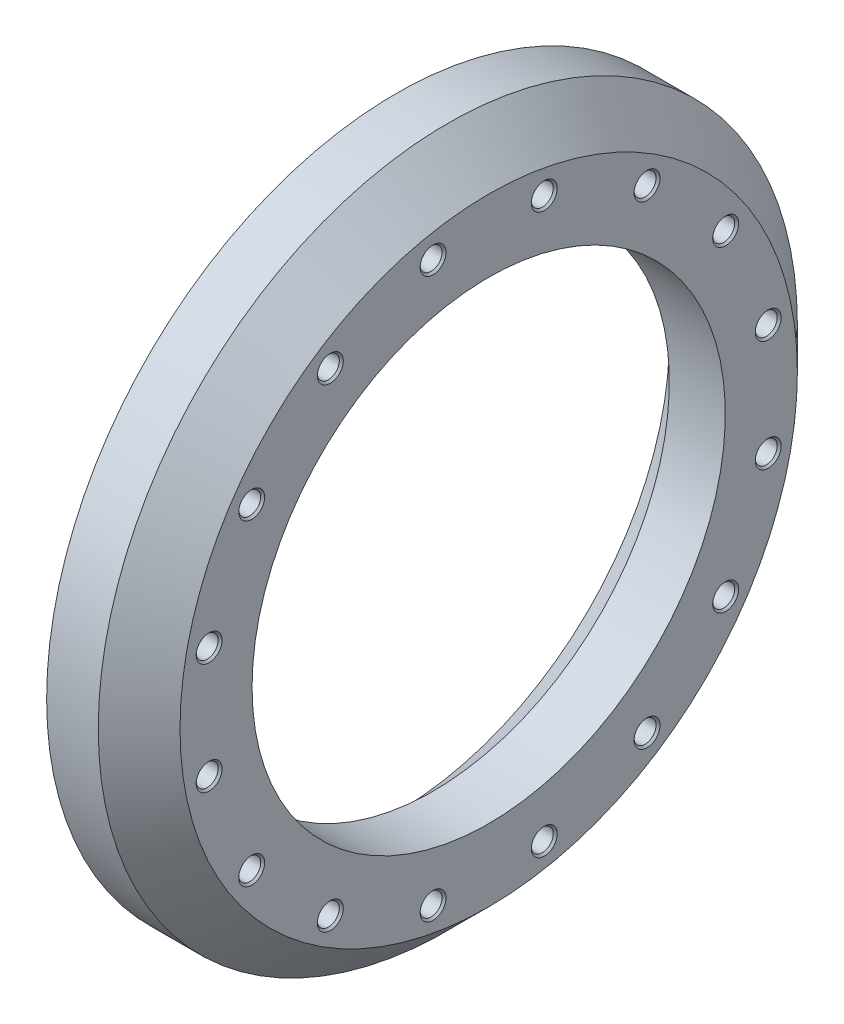
SolidWorks part; units mm, degrees
ref_plane "Front Plane" through (0, 0, 0) normal (0, 0, 1) x (1, 0, 0)
ref_plane "Top Plane" through (0, 0, 0) normal (0, 1, 0) x (1, 0, 0)
ref_plane "Right Plane" through (0, 0, 0) normal (1, 0, 0) x (0, 0, -1)
sketch "Sketch1" plane through (0, 0, 0) normal (0, 0, 1) x (1, 0, 0)
  line L0 (0, 0) -> (182.7212, 0) construction
  line L2 (0, 162.5) -> (0, 127)
  line L5 (17, 110) -> (43, 110)
  line L6 (43, 110) -> (43, 143.5)
  line L7 (0, 162.5) -> (24, 162.5)
  line L8 (24, 162.5) -> (43, 143.5)
  line L10 (0, 127) -> (17, 110)
  dimension "D1" = 325
  dimension "D2" = 254
  dimension "D3" = 43
  dimension "D4" = 45
  dimension "D5" = 19
  dimension "D7" = 220
revolve "Revolve1" add sketch "Sketch1" angle 360 about L0
sketch "Sketch2" plane through (0, 0, 0) normal (-1, 0, 0) x (0, 0, 1)
  line L0 (0, 0) -> (25.8495, 129.954) construction
  circle A0 centre (0, 0) radius 152 construction
  circle A1 centre (0, 0) radius 132.5 construction
  dimension "D1" = 304
  dimension "D2" = 265
  dimension "D3" = 11.25
hole_wizard "M12 Tapped Hole1" positions "Sketch3" profile "Sketch4" tap size "M12" standard "ISO"
sketch "Sketch3" plane through (0, 0, 0) normal (-1, 0, 0) x (0, 0, 1)
  circle A0 centre (0, 0) radius 152 construction
  point P0 (0, 152)
sketch "Sketch4" plane through (0, 152, 0) normal (0, 1, 0) x (0, 0, 1)
  line L0 (0, 0) -> (0, 26.3144)
  line L1 (0, 26.3144) -> (5.1, 23.25)
  line L2 (5.1, 23.25) -> (5.1, 0.925)
  line L3 (5.1, 0.925) -> (6.025, 0)
  line L5 (6.025, 0) -> (0, 0)
  line L6 (-5.1, 0.925) -> (-6.025, 0) construction
  line L10 (0, 26.3144) -> (-5.1, 23.25) construction
  line L11 (0, -6.35) -> (0, 107.95) construction
  dimension "Tap Drill Dia." = 10.2
  dimension "Tap Drill Depth" = 23.25
  dimension "Near C'Sink Dia." = 12.05
  dimension "Near C'Sink Angle" = 90
  dimension "Drill Angle" = 118
cosmetic thread "Hole Thread1" parameters "D1"=18, "D2"=12
pattern_circular "CirPattern1" count 16 over 360 about axis through (0, 0, 0) along (1, 0, 0) of "M12 Tapped Hole1"
cosmetic thread "Hole Thread2" parameters "D1"=18, "D2"=12
cosmetic thread "Hole Thread3" parameters "D1"=18, "D2"=12
cosmetic thread "Hole Thread4" parameters "D1"=18, "D2"=12
cosmetic thread "Hole Thread5" parameters "D1"=18, "D2"=12
cosmetic thread "Hole Thread6" parameters "D1"=18, "D2"=12
cosmetic thread "Hole Thread7" parameters "D1"=18, "D2"=12
cosmetic thread "Hole Thread8" parameters "D1"=18, "D2"=12
cosmetic thread "Hole Thread9" parameters "D1"=18, "D2"=12
cosmetic thread "Hole Thread10" parameters "D1"=18, "D2"=12
cosmetic thread "Hole Thread11" parameters "D1"=18, "D2"=12
cosmetic thread "Hole Thread12" parameters "D1"=18, "D2"=12
cosmetic thread "Hole Thread13" parameters "D1"=18, "D2"=12
cosmetic thread "Hole Thread14" parameters "D1"=18, "D2"=12
cosmetic thread "Hole Thread15" parameters "D1"=18, "D2"=12
cosmetic thread "Hole Thread16" parameters "D1"=18, "D2"=12
hole_wizard "M12 Tapped Hole2" positions "Sketch5" profile "Sketch6" tap size "M12" standard "ISO"
sketch "Sketch5" plane through (43, 0, 0) normal (1, 0, 0) x (0, 0, -1)
  point P4 (-25.8495, 129.954)
sketch "Sketch6" plane through (43, 129.954, 25.8495) normal (0, 1, 0) x (0, 0, -1)
  line L0 (0, 0) -> (0, 32.3144)
  line L1 (0, 32.3144) -> (5.1, 29.25)
  line L2 (5.1, 29.25) -> (5.1, 0.925)
  line L3 (5.1, 0.925) -> (6.025, 0)
  line L5 (6.025, 0) -> (0, 0)
  line L6 (-5.1, 0.925) -> (-6.025, 0) construction
  line L10 (0, 32.3144) -> (-5.1, 29.25) construction
  line L11 (0, -6.35) -> (0, 107.95) construction
  dimension "Tap Drill Dia." = 10.2
  dimension "Tap Drill Depth" = 29.25
  dimension "Near C'Sink Dia." = 12.05
  dimension "Near C'Sink Angle" = 90
  dimension "Drill Angle" = 118
cosmetic thread "Hole Thread17" parameters "D1"=24, "D2"=12
pattern_circular "CirPattern2" count 16 over 360 about axis through (0, 0, 0) along (1, 0, 0) of "M12 Tapped Hole2"
cosmetic thread "Hole Thread18" parameters "D1"=24, "D2"=12
cosmetic thread "Hole Thread19" parameters "D1"=24, "D2"=12
cosmetic thread "Hole Thread20" parameters "D1"=24, "D2"=12
cosmetic thread "Hole Thread21" parameters "D1"=24, "D2"=12
cosmetic thread "Hole Thread22" parameters "D1"=24, "D2"=12
cosmetic thread "Hole Thread23" parameters "D1"=24, "D2"=12
cosmetic thread "Hole Thread24" parameters "D1"=24, "D2"=12
cosmetic thread "Hole Thread25" parameters "D1"=24, "D2"=12
cosmetic thread "Hole Thread26" parameters "D1"=24, "D2"=12
cosmetic thread "Hole Thread27" parameters "D1"=24, "D2"=12
cosmetic thread "Hole Thread28" parameters "D1"=24, "D2"=12
cosmetic thread "Hole Thread29" parameters "D1"=24, "D2"=12
cosmetic thread "Hole Thread30" parameters "D1"=24, "D2"=12
cosmetic thread "Hole Thread31" parameters "D1"=24, "D2"=12
cosmetic thread "Hole Thread32" parameters "D1"=24, "D2"=12
